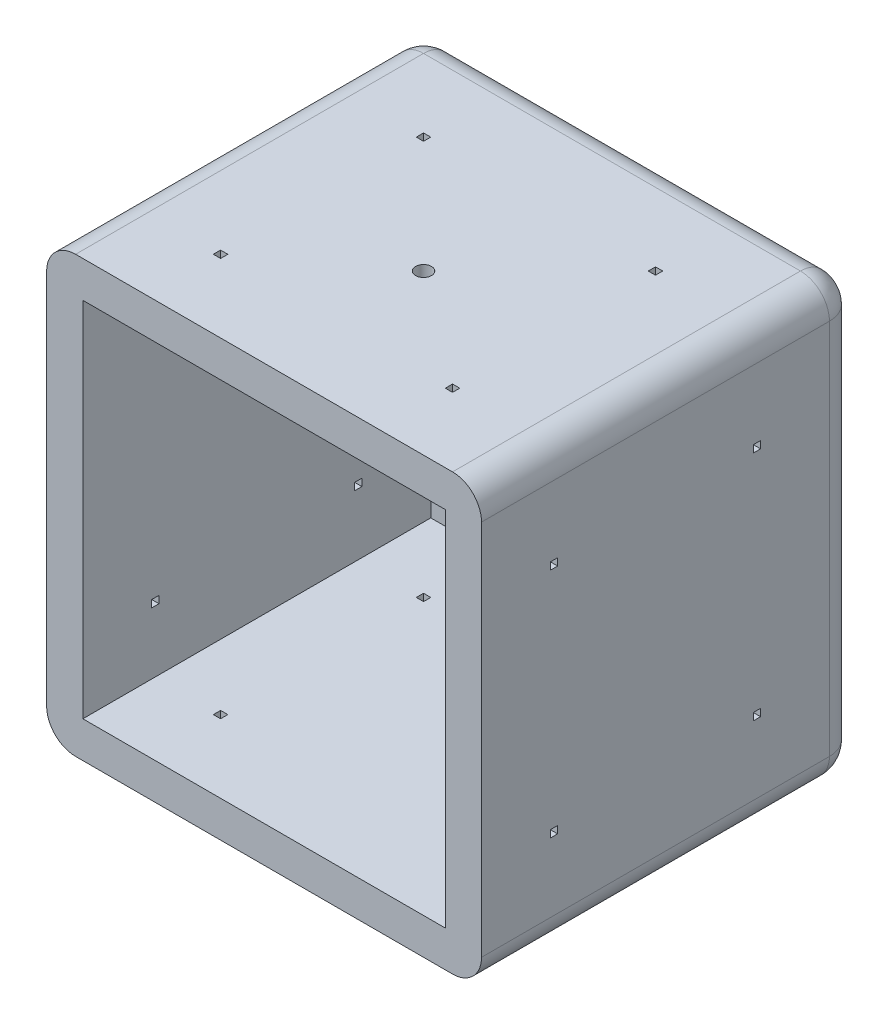
SolidWorks part; units mm, degrees
ref_plane "Front Plane" through (0, 0, 0) normal (0, 0, 1) x (1, 0, 0)
ref_plane "Top Plane" through (0, 0, 0) normal (0, 1, 0) x (1, 0, 0)
ref_plane "Right Plane" through (0, 0, 0) normal (1, 0, 0) x (0, 0, -1)
sketch "Sketch1" plane through (0, 0, 0) normal (0, 0, 1) x (1, 0, 0)
  line L1 (0, 0) -> (300, 0)
  line L2 (0, 0) -> (0, 300)
  line L3 (0, 300) -> (300, 300)
  line L4 (300, 0) -> (300, 300)
  dimension "D1" = 300
  dimension "D2" = 300
extrude "Boss-Extrude1" add sketch "Sketch1" along normal blind 260
fillet "Fillet1" radius 20 8 edges at (0, 300, 130) (0, 150, 0) (150, 300, 0) (300, 300, 130) (300, 150, 0) (300, 0, 130) (150, 0, 0) (0, 0, 130)
sketch "Sketch2" plane through (0, 0, 260) normal (0, 0, 1) x (1, 0, 0)
  line L0 (0, 280) -> (0, 20) construction
  line L1 (25, 275) -> (275, 275)
  line L2 (25, 275) -> (25, 25)
  line L3 (25, 25) -> (275, 25)
  line L4 (275, 275) -> (275, 25)
  line L5 (280, 300) -> (20, 300) construction
  line L6 (300, 20) -> (300, 280) construction
  line L7 (20, 0) -> (280, 0) construction
  dimension "D1" = 25
  dimension "D2" = 25
  dimension "D3" = 25
  dimension "D4" = 25
extrude "Cut-Extrude1" cut sketch "Sketch2" against normal blind 240
sketch "Sketch3" plane through (0, 300, 0) normal (0, 1, 0) x (1, 0, 0)
  line L0 (20, 0) -> (280, 0) construction
  line L1 (300, -20) -> (300, -260) construction
  circle A0 centre (150, -150) radius 5.5
  dimension "D3" = 11
  dimension "D1" = 150
  dimension "D2" = 150
extrude "Cut-Extrude2" cut sketch "Sketch3" against normal up to surface (25 mm away) up to face at (150, 275, 140)
sketch "Sketch4" plane through (0, 300, 0) normal (0, 1, 0) x (1, 0, 0)
  line L0 (0, -260) -> (0, -20) construction
  line L1 (67.5, -67.5) -> (72.5, -67.5)
  line L2 (67.5, -67.5) -> (67.5, -72.5)
  line L3 (67.5, -72.5) -> (72.5, -72.5)
  line L4 (72.5, -67.5) -> (72.5, -72.5)
  line L5 (67.5, -67.5) -> (72.5, -72.5) construction
  line L6 (67.5, -72.5) -> (72.5, -67.5) construction
  line L7 (20, 0) -> (280, 0) construction
  line L9 (67.5, -207.5) -> (72.5, -207.5)
  line L10 (67.5, -207.5) -> (67.5, -212.5)
  line L11 (67.5, -212.5) -> (72.5, -212.5)
  line L12 (72.5, -207.5) -> (72.5, -212.5)
  line L13 (67.5, -207.5) -> (72.5, -212.5) construction
  line L14 (67.5, -212.5) -> (72.5, -207.5) construction
  line L16 (232.5, -67.5) -> (227.5, -67.5)
  line L17 (232.5, -67.5) -> (232.5, -72.5)
  line L18 (232.5, -72.5) -> (227.5, -72.5)
  line L19 (227.5, -67.5) -> (227.5, -72.5)
  line L20 (232.5, -67.5) -> (227.5, -72.5) construction
  line L21 (232.5, -72.5) -> (227.5, -67.5) construction
  line L22 (232.5, -207.5) -> (227.5, -207.5)
  line L23 (232.5, -207.5) -> (232.5, -212.5)
  line L24 (232.5, -212.5) -> (227.5, -212.5)
  line L25 (227.5, -207.5) -> (227.5, -212.5)
  line L26 (232.5, -207.5) -> (227.5, -212.5) construction
  line L27 (232.5, -212.5) -> (227.5, -207.5) construction
  point P0 (70, -70)
  point P9 (70, -210)
  point P16 (230, -70)
  point P21 (230, -210)
  dimension "D1" = 70
  dimension "D2" = 5
  dimension "D3" = 5
  dimension "D4" = 70
  dimension "D5" = 140
  dimension "D6" = 160
  dimension "D7" = 5
  dimension "D8" = 5
  dimension "D13" = 5
  dimension "D14" = 5
  dimension "D15" = 5
  dimension "D16" = 5
sketch "Sketch6" plane through (300, 0, 0) normal (1, 0, 0) x (0, 0, -1)
  line L0 (-212.5, 232.5) -> (-207.5, 232.5)
  line L1 (-212.5, 232.5) -> (-212.5, 227.5)
  line L2 (-212.5, 227.5) -> (-207.5, 227.5)
  line L3 (-207.5, 232.5) -> (-207.5, 227.5)
  line L4 (-212.5, 232.5) -> (-207.5, 227.5) construction
  line L5 (-212.5, 227.5) -> (-207.5, 232.5) construction
  line L6 (-212.5, 72.5) -> (-207.5, 72.5)
  line L7 (-212.5, 72.5) -> (-212.5, 67.5)
  line L8 (-212.5, 67.5) -> (-207.5, 67.5)
  line L9 (-207.5, 72.5) -> (-207.5, 67.5)
  line L10 (-212.5, 72.5) -> (-207.5, 67.5) construction
  line L11 (-212.5, 67.5) -> (-207.5, 72.5) construction
  line L12 (-67.5, 232.5) -> (-72.5, 232.5)
  line L13 (-67.5, 232.5) -> (-67.5, 227.5)
  line L14 (-67.5, 227.5) -> (-72.5, 227.5)
  line L15 (-72.5, 232.5) -> (-72.5, 227.5)
  line L16 (-67.5, 232.5) -> (-72.5, 227.5) construction
  line L17 (-67.5, 227.5) -> (-72.5, 232.5) construction
  line L18 (-67.5, 72.5) -> (-72.5, 72.5)
  line L19 (-67.5, 72.5) -> (-67.5, 67.5)
  line L20 (-67.5, 67.5) -> (-72.5, 67.5)
  line L21 (-72.5, 72.5) -> (-72.5, 67.5)
  line L22 (-67.5, 72.5) -> (-72.5, 67.5) construction
  line L23 (-67.5, 67.5) -> (-72.5, 72.5) construction
  line L24 (0, 280) -> (0, 20) construction
  line L25 (-20, 0) -> (-260, 0) construction
  point P0 (-210, 230)
  point P5 (-210, 70)
  point P10 (-70, 230)
  point P15 (-70, 70)
  dimension "D1" = 5
  dimension "D2" = 5
  dimension "D3" = 5
  dimension "D4" = 5
  dimension "D5" = 5
  dimension "D6" = 5
  dimension "D7" = 5
  dimension "D8" = 5
  dimension "D9" = 160
  dimension "D10" = 140
  dimension "D11" = 70
  dimension "D12" = 70
sketch "Sketch7" plane through (0, 0, 0) normal (0, -1, 0) x (1, 0, 0)
  line L0 (67.5, 212.5) -> (72.5, 212.5)
  line L1 (67.5, 212.5) -> (67.5, 207.5)
  line L2 (67.5, 207.5) -> (72.5, 207.5)
  line L3 (72.5, 212.5) -> (72.5, 207.5)
  line L4 (67.5, 212.5) -> (72.5, 207.5) construction
  line L5 (67.5, 207.5) -> (72.5, 212.5) construction
  line L6 (67.5, 72.5) -> (72.5, 72.5)
  line L7 (67.5, 72.5) -> (67.5, 67.5)
  line L8 (67.5, 67.5) -> (72.5, 67.5)
  line L9 (72.5, 72.5) -> (72.5, 67.5)
  line L10 (67.5, 72.5) -> (72.5, 67.5) construction
  line L11 (67.5, 67.5) -> (72.5, 72.5) construction
  line L12 (232.5, 212.5) -> (227.5, 212.5)
  line L13 (232.5, 212.5) -> (232.5, 207.5)
  line L14 (232.5, 207.5) -> (227.5, 207.5)
  line L15 (227.5, 212.5) -> (227.5, 207.5)
  line L16 (232.5, 212.5) -> (227.5, 207.5) construction
  line L17 (232.5, 207.5) -> (227.5, 212.5) construction
  line L18 (232.5, 72.5) -> (227.5, 72.5)
  line L19 (232.5, 72.5) -> (232.5, 67.5)
  line L20 (232.5, 67.5) -> (227.5, 67.5)
  line L21 (227.5, 72.5) -> (227.5, 67.5)
  line L22 (232.5, 72.5) -> (227.5, 67.5) construction
  line L23 (232.5, 67.5) -> (227.5, 72.5) construction
  line L24 (280, 0) -> (20, 0) construction
  line L25 (0, 20) -> (0, 260) construction
  point P0 (70, 210)
  point P5 (70, 70)
  point P10 (230, 210)
  point P15 (230, 70)
  dimension "D1" = 5
  dimension "D2" = 5
  dimension "D3" = 5
  dimension "D4" = 5
  dimension "D5" = 5
  dimension "D6" = 5
  dimension "D7" = 5
  dimension "D8" = 5
  dimension "D9" = 140
  dimension "D10" = 160
  dimension "D11" = 70
  dimension "D12" = 70
sketch "Sketch8" plane through (0, 0, 0) normal (-1, 0, 0) x (0, 0, 1)
  line L0 (67.5, 232.5) -> (72.5, 232.5)
  line L1 (67.5, 232.5) -> (67.5, 227.5)
  line L2 (67.5, 227.5) -> (72.5, 227.5)
  line L3 (72.5, 232.5) -> (72.5, 227.5)
  line L4 (67.5, 232.5) -> (72.5, 227.5) construction
  line L5 (67.5, 227.5) -> (72.5, 232.5) construction
  line L6 (67.5, 72.5) -> (72.5, 72.5)
  line L7 (67.5, 72.5) -> (67.5, 67.5)
  line L8 (67.5, 67.5) -> (72.5, 67.5)
  line L9 (72.5, 72.5) -> (72.5, 67.5)
  line L10 (67.5, 72.5) -> (72.5, 67.5) construction
  line L11 (67.5, 67.5) -> (72.5, 72.5) construction
  line L12 (212.5, 232.5) -> (207.5, 232.5)
  line L13 (212.5, 232.5) -> (212.5, 227.5)
  line L14 (212.5, 227.5) -> (207.5, 227.5)
  line L15 (207.5, 232.5) -> (207.5, 227.5)
  line L16 (212.5, 232.5) -> (207.5, 227.5) construction
  line L17 (212.5, 227.5) -> (207.5, 232.5) construction
  line L18 (212.5, 72.5) -> (207.5, 72.5)
  line L19 (212.5, 72.5) -> (212.5, 67.5)
  line L20 (212.5, 67.5) -> (207.5, 67.5)
  line L21 (207.5, 72.5) -> (207.5, 67.5)
  line L22 (212.5, 72.5) -> (207.5, 67.5) construction
  line L23 (212.5, 67.5) -> (207.5, 72.5) construction
  line L24 (260, 0) -> (20, 0) construction
  line L25 (0, 20) -> (0, 280) construction
  point P0 (70, 230)
  point P5 (70, 70)
  point P10 (210, 230)
  point P15 (210, 70)
  dimension "D1" = 5
  dimension "D2" = 5
  dimension "D3" = 5
  dimension "D4" = 5
  dimension "D5" = 5
  dimension "D6" = 5
  dimension "D7" = 5
  dimension "D8" = 5
  dimension "D9" = 160
  dimension "D10" = 140
  dimension "D11" = 70
  dimension "D12" = 70
sketch "Sketch9" plane through (0, 0, 0) normal (0, 0, -1) x (-1, 0, 0)
  line L0 (-232.5, 232.5) -> (-227.5, 232.5)
  line L1 (-232.5, 232.5) -> (-232.5, 227.5)
  line L2 (-232.5, 227.5) -> (-227.5, 227.5)
  line L3 (-227.5, 232.5) -> (-227.5, 227.5)
  line L4 (-232.5, 232.5) -> (-227.5, 227.5) construction
  line L5 (-232.5, 227.5) -> (-227.5, 232.5) construction
  line L6 (-232.5, 72.5) -> (-227.5, 72.5)
  line L7 (-232.5, 72.5) -> (-232.5, 67.5)
  line L8 (-232.5, 67.5) -> (-227.5, 67.5)
  line L9 (-227.5, 72.5) -> (-227.5, 67.5)
  line L10 (-232.5, 72.5) -> (-227.5, 67.5) construction
  line L11 (-232.5, 67.5) -> (-227.5, 72.5) construction
  line L12 (-67.5, 232.5) -> (-72.5, 232.5)
  line L13 (-67.5, 232.5) -> (-67.5, 227.5)
  line L14 (-67.5, 227.5) -> (-72.5, 227.5)
  line L15 (-72.5, 232.5) -> (-72.5, 227.5)
  line L16 (-67.5, 232.5) -> (-72.5, 227.5) construction
  line L17 (-67.5, 227.5) -> (-72.5, 232.5) construction
  line L18 (-67.5, 72.5) -> (-72.5, 72.5)
  line L19 (-67.5, 72.5) -> (-67.5, 67.5)
  line L20 (-67.5, 67.5) -> (-72.5, 67.5)
  line L21 (-72.5, 72.5) -> (-72.5, 67.5)
  line L22 (-67.5, 72.5) -> (-72.5, 67.5) construction
  line L23 (-67.5, 67.5) -> (-72.5, 72.5) construction
  line L24 (-280, 300) -> (-20, 300) construction
  line L25 (-300, 20) -> (-300, 280) construction
  point P0 (-230, 230)
  point P5 (-230, 70)
  point P10 (-70, 230)
  point P15 (-70, 70)
  dimension "D1" = 5
  dimension "D2" = 5
  dimension "D3" = 5
  dimension "D4" = 5
  dimension "D5" = 5
  dimension "D6" = 5
  dimension "D7" = 5
  dimension "D8" = 5
  dimension "D9" = 160
  dimension "D10" = 160
  dimension "D11" = 70
  dimension "D12" = 70
extrude "Cut-Extrude3" cut sketch "Sketch4" against normal up to surface (25 mm away) up to face at (150, 275, 155.5)
extrude "Cut-Extrude4" cut sketch "Sketch6" against normal up to surface (25 mm away) up to face at (275, 150, 140)
extrude "Cut-Extrude5" cut sketch "Sketch7" against normal up to surface (25 mm away) up to face at (150, 25, 140)
extrude "Cut-Extrude6" cut sketch "Sketch8" against normal up to surface (25 mm away) up to face at (25, 150, 140)
extrude "Cut-Extrude7" cut sketch "Sketch9" against normal up to surface (20 mm away) up to face at (150, 150, 20)
